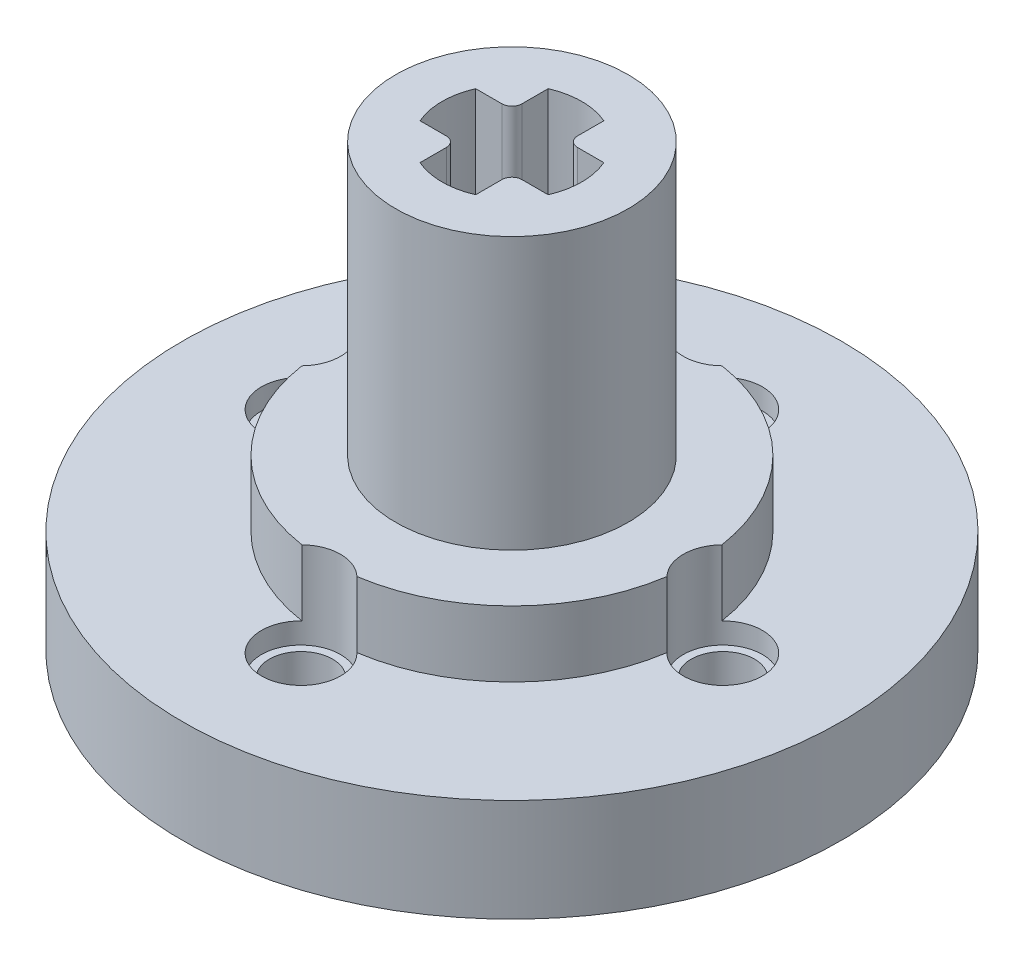
SolidWorks part; units mm, degrees
ref_plane "Front Plane" through (0, 0, 0) normal (0, 0, 1) x (1, 0, 0)
ref_plane "Top Plane" through (0, 0, 0) normal (0, 1, 0) x (1, 0, 0)
ref_plane "Right Plane" through (0, 0, 0) normal (1, 0, 0) x (0, 0, -1)
sketch "Sketch1" plane through (0, 0, 0) normal (0, 0, 1) x (1, 0, 0)
  line L0 (0, 0) -> (0, 16.7)
  line L1 (0, 0) -> (12.5, 0)
  line L2 (12.5, 0) -> (12.5, 3.9)
  line L3 (12.5, 3.9) -> (7, 3.9)
  line L6 (7, 3.9) -> (7, 6.4)
  line L7 (7, 6.4) -> (4.41, 6.4)
  line L8 (4.41, 6.4) -> (4.41, 16.7)
  line L13 (4.41, 16.7) -> (0, 16.7)
  dimension "D1" = 16.7
  dimension "D4" = 2.5
  dimension "D6" = 3.9
  dimension "D7" = 8.82
  dimension "D9" = 7
  dimension "D11" = 12.5
revolve "Revolve1" add sketch "Sketch1" angle 360 about L0
sketch "Sketch2" plane through (0, 16.7, 0) normal (0, 1, 0) x (1, 0, 0)
  line L0 (0.935, -1.435) -> (0.935, -2.35) construction
  line L1 (-0.935, 2.35) -> (0.935, 2.35) construction
  line L2 (-0.935, 2.35) -> (-0.935, 1.435) construction
  line L3 (-0.935, -2.35) -> (0.935, -2.35) construction
  line L4 (0.935, 2.35) -> (0.935, 1.435) construction
  line L5 (0, -2.35) -> (0, 0) construction
  line L6 (0, 0) -> (0, 2.35) construction
  line L7 (-2.35, 0.935) -> (-1.435, 0.935) construction
  line L8 (-2.35, 0.935) -> (-2.35, -0.935) construction
  line L9 (-2.35, -0.935) -> (-1.435, -0.935) construction
  line L10 (2.35, 0.935) -> (2.35, -0.935) construction
  line L11 (0, 0) -> (2.35, 0) construction
  line L12 (-2.35, 0) -> (0, 0) construction
  line L13 (1.435, -0.935) -> (2.35, -0.935) construction
  line L14 (-0.935, -1.435) -> (-0.935, -2.35) construction
  line L15 (1.435, 0.935) -> (2.35, 0.935) construction
  line L16 (1.055, -1.435) -> (1.055, -2.43)
  line L17 (1.435, -1.055) -> (2.43, -1.055)
  line L18 (1.435, 1.055) -> (2.43, 1.055)
  line L19 (1.055, 2.43) -> (1.055, 1.435)
  line L20 (-1.055, 2.43) -> (-1.055, 1.435)
  line L21 (-2.43, 1.055) -> (-1.435, 1.055)
  line L22 (-2.43, -1.055) -> (-1.435, -1.055)
  line L23 (-1.055, -1.435) -> (-1.055, -2.43)
  arc A0 (-0.935, 1.435) -> (-1.435, 0.935) centre (-1.435, 1.435) cw construction
  arc A1 (-1.435, -0.935) -> (-0.935, -1.435) centre (-1.435, -1.435) cw construction
  arc A2 (0.935, -1.435) -> (1.435, -0.935) centre (1.435, -1.435) cw construction
  arc A3 (0.935, 1.435) -> (1.435, 0.935) centre (1.435, 1.435) ccw construction
  arc A4 (2.35, -0.935) -> (2.35, 0.935) centre (0, 0) ccw construction
  arc A5 (0.935, 2.35) -> (-0.935, 2.35) centre (0, 0) ccw construction
  arc A6 (-2.35, 0.935) -> (-2.35, -0.935) centre (0, 0) ccw construction
  arc A7 (-0.935, -2.35) -> (0.935, -2.35) centre (0, 0) ccw construction
  arc A8 (-1.055, -2.43) -> (1.055, -2.43) centre (0, 0) ccw
  arc A9 (1.055, -1.435) -> (1.435, -1.055) centre (1.435, -1.435) cw
  arc A10 (2.43, -1.055) -> (2.43, 1.055) centre (0, 0) ccw
  arc A11 (1.055, 1.435) -> (1.435, 1.055) centre (1.435, 1.435) ccw
  arc A12 (1.055, 2.43) -> (-1.055, 2.43) centre (0, 0) ccw
  arc A13 (-1.055, 1.435) -> (-1.435, 1.055) centre (-1.435, 1.435) cw
  arc A14 (-2.43, 1.055) -> (-2.43, -1.055) centre (0, 0) ccw
  arc A15 (-1.435, -1.055) -> (-1.055, -1.435) centre (-1.435, -1.435) cw
  point P0 (0, 0)
  point P4 (0, 0)
  point P22 (-0.935, -0.935)
  point P27 (0.935, -0.935)
  point P30 (0.935, 0.935)
  dimension "D3" = 0.5
  dimension "D4" = 0.12
  dimension "D1" = 1.87
  dimension "D2" = 2.35
extrude "Cut-Extrude1" cut sketch "Sketch2" against normal up to next contours L14 A7 L0 A2 L13 A4 L15 A3 L4 A5 L2 A0 L7 A6 L9 A1 | L22 A15 L23 A8 L16 A9 L17 A10 L18 A11 L19 A12 L20 A13 L21 A14
sketch "Sketch3" plane through (0, 3.9, 0) normal (0, 1, 0) x (1, 0, 0)
  line L0 (0, 0) -> (0, 8) construction
  line L2 (0, 0) -> (-8, 0) construction
  circle A0 centre (0, 8) radius 1.5
  circle A2 centre (0, -8) radius 1.5
  circle A3 centre (-8, 0) radius 1.5
  circle A4 centre (8, 0) radius 1.5
  point P10 (0, 0)
  dimension "D1" = 8
  dimension "D2" = 3
extrude "Cut-Extrude2" cut sketch "Sketch3" against normal blind 0.7937 and the other way up to surface other way up to face at (0, 6.4, -4.41)
sketch "Sketch5" plane through (0, 3.9, 0) normal (0, 1, 0) x (1, 0, 0)
  circle A0 centre (8, 0) radius 1.2
  circle A1 centre (0, 8) radius 1.2
  circle A2 centre (-8, 0) radius 1.2
  circle A3 centre (0, -8) radius 1.2
  dimension "D1" = 2.4
extrude "Cut-Extrude3" cut sketch "Sketch5" against normal up to next
